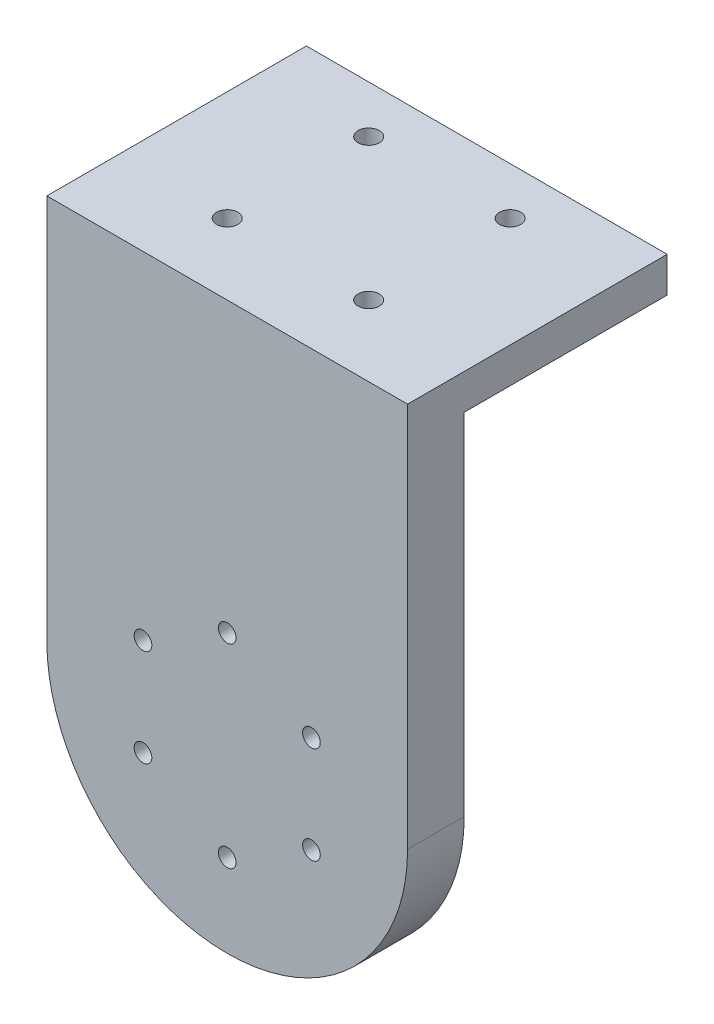
SolidWorks part; units mm, degrees
ref_plane "정면" through (0, 0, 0) normal (0, 0, 1) x (1, 0, 0)
ref_plane "윗면" through (0, 0, 0) normal (0, 1, 0) x (1, 0, 0)
ref_plane "우측면" through (0, 0, 0) normal (1, 0, 0) x (0, 0, -1)
sketch "스케치1" plane through (0, 0, 0) normal (0, 0, 1) x (1, 0, 0)
  line L2 (0, 0) -> (0, 54.5)
  line L3 (0, 54.5) -> (51, 54.5)
  line L4 (51, 0) -> (51, 54.5)
  arc A1 (0, 0) -> (51, 0) centre (25.5, 0) ccw
  dimension "D1" = 51
  dimension "D2" = 54.5
extrude "보스-돌출1" add sketch "스케치1" along normal blind 8
sketch "스케치2" plane through (0, 0, 0) normal (0, 0, -1) x (-1, 0, 0)
  line L0 (0, 54.5) -> (0, 0) construction
  line L1 (-51, 54.5) -> (0, 54.5)
  line L2 (-51, 54.5) -> (-51, 49.5)
  line L3 (-51, 49.5) -> (0, 49.5)
  line L4 (0, 54.5) -> (0, 49.5)
  dimension "D1" = 5
extrude "보스-돌출2" add sketch "스케치2" along normal blind 28.7
sketch "스케치3" plane through (0, 0, 0) normal (0, 0, -1) x (-1, 0, 0)
  circle A0 centre (-25.5, 0) radius 17.5
  dimension "D1" = 35
extrude "컷-돌출1" cut sketch "스케치3" against normal blind 2
sketch "스케치4" plane through (0, 0, 2) normal (0, 0, -1) x (-1, 0, 0)
  circle A0 centre (-25.5, 0) radius 13.75 construction
  circle A1 centre (-25.5, 13.75) radius 1.25
  circle A2 centre (-13.5922, 6.875) radius 1.25
  circle A3 centre (-13.5922, -6.875) radius 1.25
  circle A4 centre (-25.5, -13.75) radius 1.25
  circle A5 centre (-37.4078, -6.875) radius 1.25
  circle A6 centre (-37.4078, 6.875) radius 1.25
  point P18 (-25.5, 0)
  dimension "D1" = 27.5
  dimension "D2" = 2.5
  dimension "D3" = 6
extrude "컷-돌출2" cut sketch "스케치4" against normal up to next
sketch "스케치5" plane through (0, 54.5, 0) normal (0, 1, 0) x (1, 0, 0)
  line L0 (51, -8) -> (0, -8) construction
  line L1 (15.5, 22) -> (35.5, 22) construction
  line L2 (15.5, 22) -> (15.5, 2) construction
  line L3 (15.5, 2) -> (35.5, 2) construction
  line L4 (35.5, 22) -> (35.5, 2) construction
  line L5 (15.5, 22) -> (35.5, 2) construction
  line L6 (15.5, 2) -> (35.5, 22) construction
  line L8 (0, -8) -> (0, 28.7) construction
  circle A0 centre (15.5, 22) radius 1.5
  circle A1 centre (35.5, 22) radius 1.5
  circle A2 centre (35.5, 2) radius 1.5
  circle A3 centre (15.5, 2) radius 1.5
  point P0 (25.5, 12)
  dimension "D5" = 3
  dimension "D1" = 20
  dimension "D2" = 20
  dimension "D3" = 10
  dimension "D4" = 15.5
extrude "컷-돌출3" cut sketch "스케치5" against normal blind 5
